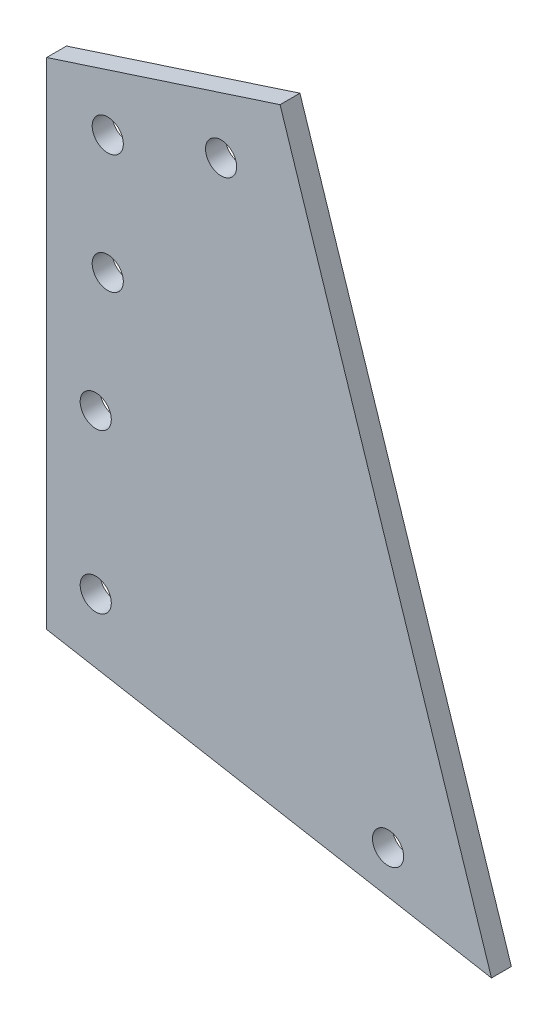
SolidWorks part; units mm, degrees
ref_plane "Front Plane" through (0, 0, 0) normal (0, 0, 1) x (1, 0, 0)
ref_plane "Top Plane" through (0, 0, 0) normal (0, 1, 0) x (1, 0, 0)
ref_plane "Right Plane" through (0, 0, 0) normal (1, 0, 0) x (0, 0, -1)
sketch "Sketch2" plane through (0, 0, 0) normal (0, 0, 1) x (1, 0, 0)
  line L0 (40.992, 298.8407) -> (42.1693, 295.2171) construction
  line L2 (40.992, 297.6034) -> (52.5693, 261.972) construction
  line L6 (201.5046, -196.4039) -> (40.992, 297.6034) construction
  line L7 (75.9661, 191.2015) -> (42.1693, 295.2171)
  line L8 (4.8542, 283.0927) -> (4.8542, 203.9015)
  line L9 (4.8542, 203.9015) -> (75.9661, 191.2015)
  line L10 (12.7, 238.125) -> (12.7, 212.725) construction
  line L11 (52.3102, 180.5731) -> (64.7523, 184.6158) construction
  line L12 (177.3478, -204.253) -> (25.4, 263.3943) construction
  line L13 (64.7523, 184.6158) -> (29.6006, 292.8015) construction
  line L14 (42.1693, 295.2171) -> (4.8542, 283.0927)
  dimension "D1" = 109.3686
extrude "Boss-Extrude1" add sketch "Sketch2" along normal blind 3.175
sketch "Sketch3" plane through (0, 0, 3.175) normal (0, 0, 1) x (1, 0, 0)
  line L0 (75.9661, 191.2015) -> (63.8876, 187.2769) construction
  line L1 (63.8876, 187.2769) -> (29.6006, 292.8015) construction
  line L3 (61.7899, 193.7332) -> (59.4352, 200.9803) construction
  line L4 (4.8542, 203.9015) -> (75.9661, 191.2015) construction
  line L5 (29.6006, 292.8015) -> (32.7403, 283.1387) construction
  line L6 (32.7403, 283.1387) -> (14.6226, 277.2519) construction
  line L7 (14.6226, 277.2519) -> (14.6226, 258.2019) construction
  dimension "D1" = 86.3865
hole_wizard "#10 Clearance Hole1" positions "Sketch4" profile "Sketch5" hole size "#10" standard "ANSI Inch" end condition through all
sketch "Sketch4" plane through (0, 0, 3.175) normal (0, 0, 1) x (1, 0, 0)
  point P0 (32.7403, 283.1387)
  point P3 (59.4352, 200.9803)
  point P7 (12.7, 238.125)
  point P10 (12.7, 212.725)
  point P14 (14.6226, 277.2519)
  point P17 (14.6226, 258.2019)
sketch "Sketch5" plane through (32.7403, 283.1387, 3.175) normal (1, 0, 0) x (0, -1, 0)
  line L0 (0, 0) -> (0, 3.175)
  line L1 (0, 3.175) -> (2.4892, 3.175)
  line L2 (2.4892, 3.175) -> (2.4892, 0)
  line L5 (2.4892, 0) -> (0, 0)
  line L11 (0, -6.35) -> (0, 107.95) construction
  dimension "Thru Hole Dia." = 4.9784
  dimension "Thru Hole Depth" = 3.175
